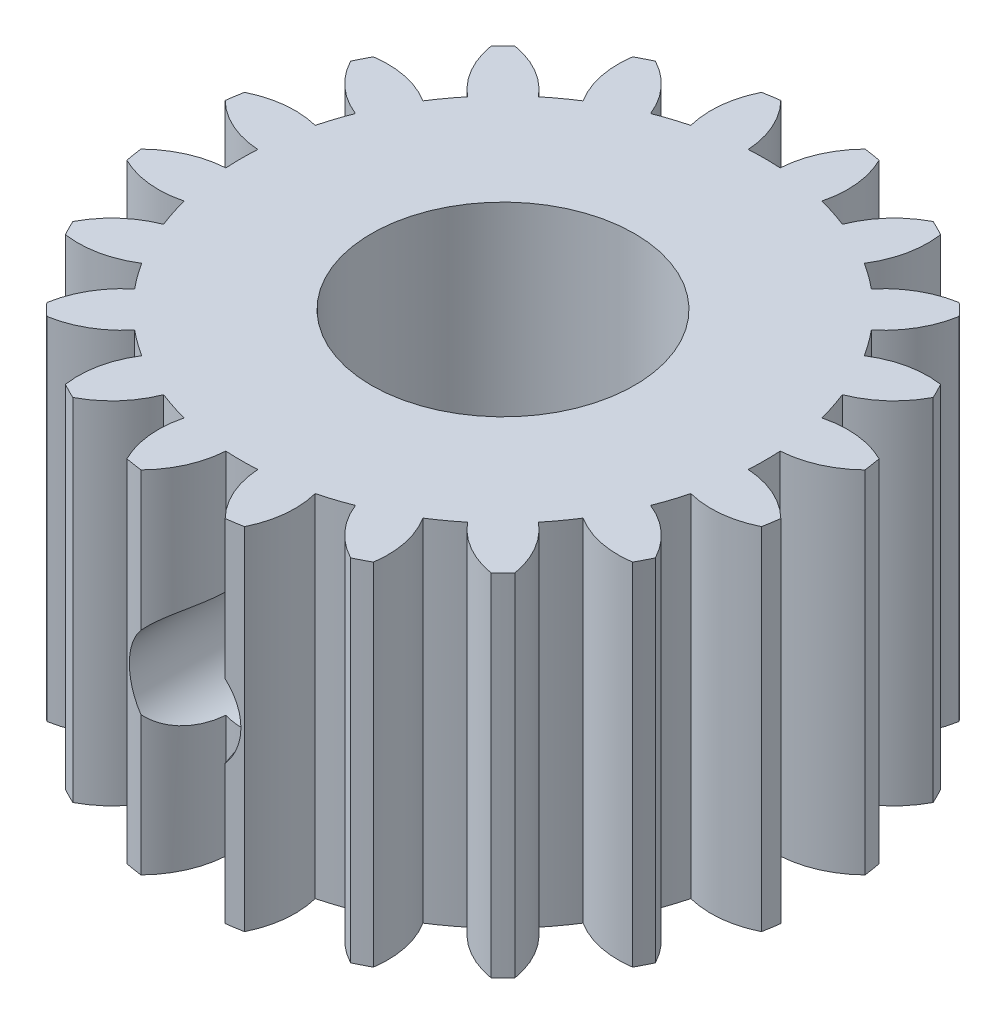
SolidWorks part; units mm, degrees
ref_plane "Front Plane" through (0, 0, 0) normal (0, 0, 1) x (1, 0, 0)
ref_plane "Top Plane" through (0, 0, 0) normal (0, 1, 0) x (1, 0, 0)
ref_plane "Right Plane" through (0, 0, 0) normal (1, 0, 0) x (0, 0, -1)
sketch "Sketch1" plane through (0, 0, 0) normal (0, 1, 0) x (1, 0, 0)
  circle A0 centre (0, 0) radius 11.684
  dimension "D1" = 23.368
extrude "Boss-Extrude1" add sketch "Sketch1" along normal blind 12.7
hole_wizard "3/8 (0.375) Diameter Hole1" positions "Sketch4" profile "Sketch5" hole size "3/8" standard "ANSI Inch" end condition through all
sketch "Sketch4" plane through (0, 12.7, 0) normal (0, 1, 0) x (1, 0, 0)
  point P0 (0, 0)
sketch "Sketch5" plane through (0, 12.7, 0) normal (1, 0, 0) x (0, 0, 1)
  line L0 (0, 0) -> (0, 12.7)
  line L1 (0, 12.7) -> (4.7625, 12.7)
  line L2 (4.7625, 12.7) -> (4.7625, 0)
  line L5 (4.7625, 0) -> (0, 0)
  line L11 (0, -6.35) -> (0, 107.95) construction
  dimension "Thru Hole Dia." = 9.525
  dimension "Thru Hole Depth" = 12.7
sketch "Sketch6" plane through (0, 12.7, 0) normal (0, 1, 0) x (1, 0, 0)
  line L0 (0, -8.0769) -> (0, 48.8756) construction
  line L1 (-0.5784, 9.4565) -> (-1.124, 9.4232) construction
  line L2 (-0.5784, 9.4565) -> (-1.1293, 18.4644) construction
  circle A0 centre (0, 0) radius 11.684 construction
  circle A1 centre (0, 0) radius 11.684 construction
  arc A2 (-1.5251, 11.584) -> (1.5251, 11.584) centre (0, 0) cw
  arc A3 (-0.5784, 9.4565) -> (0.5784, 9.4565) centre (0, 0) cw
  arc A4 (-0.5784, 9.4565) -> (-1.5251, 11.584) centre (-3.8987, 9.2534) ccw
  arc A5 (0.5784, 9.4565) -> (1.5251, 11.584) centre (3.8987, 9.2534) cw
  point P10 (0, 11.684)
  point P11 (0, 9.4742)
  dimension "D2" = 15
  dimension "D3" = 9.4742
  dimension "D1" = 7
extrude "Cut-Extrude1" cut sketch "Sketch6" against normal through all
pattern_circular "CirPattern1" count 20 over 360 about axis through (0, 0, 0) along (0, 1, 0) of "Cut-Extrude1"
ref_plane "Plane2" through (0, 0, 11.584) normal (0, 0, 1) x (1, 0, 0)
hole_wizard "#10-32 Tapped Hole2" positions "Sketch8" profile "Sketch9" tap size "#10-32" standard "ANSI Inch"
sketch "Sketch8" plane through (0, 0, 11.584) normal (0, 0, 1) x (1, 0, 0)
  line L0 (0, 0) -> (0, 12.7) construction
  line L2 (0.5784, 12.7) -> (-0.5784, 12.7) construction
  line L3 (0.5784, 12.7) -> (-0.5784, 12.7) construction
  point P0 (0, 6.35)
  point P14 (0, 6.35)
sketch "Sketch9" plane through (0, 6.35, 11.584) normal (1, 0, 0) x (0, -1, 0)
  line L0 (0, 0) -> (0, 6.8215)
  line L1 (0, 6.8215) -> (2.0193, 6.8215)
  line L2 (2.0193, 6.8215) -> (2.0193, 0)
  line L5 (2.0193, 0) -> (0, 0)
  line L11 (0, -6.35) -> (0, 107.95) construction
  dimension "Thru Tap Drill Dia." = 4.0386
  dimension "Thru Tap Drill Depth" = 6.8215
cosmetic thread "Hole Thread3" parameters "D2"=4.826
